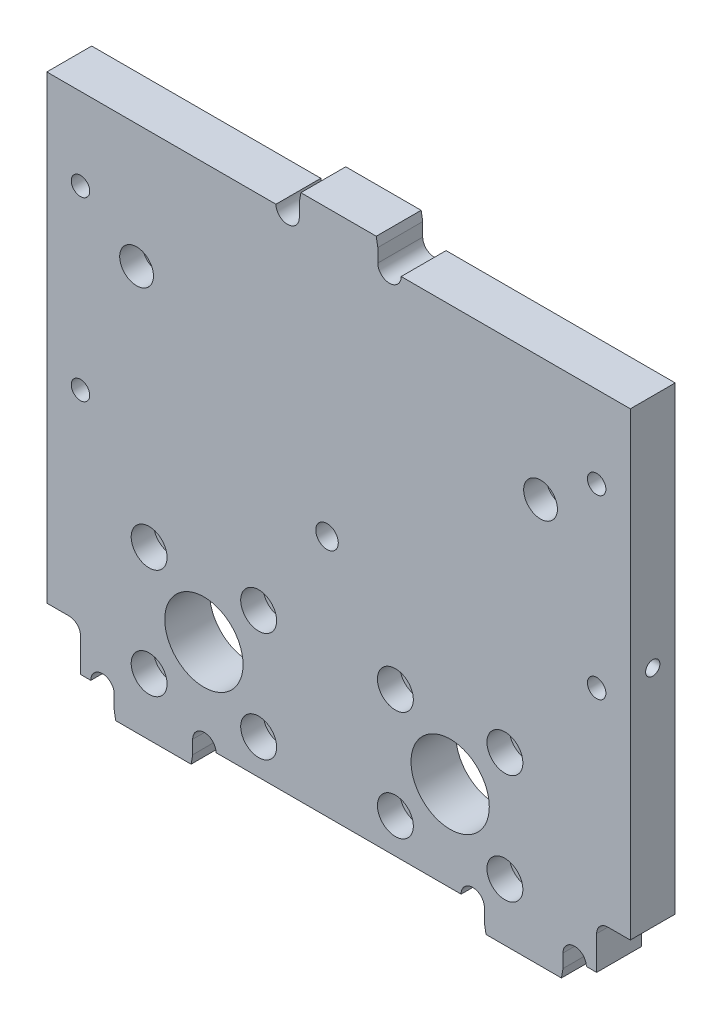
SolidWorks part; units mm, degrees
material "PE High Density"
ref_plane "Front Plane" through (0, 0, 0) normal (0, 0, 1) x (1, 0, 0)
ref_plane "Top Plane" through (0, 0, 0) normal (0, 1, 0) x (1, 0, 0)
ref_plane "Right Plane" through (0, 0, 0) normal (1, 0, 0) x (0, 0, -1)
sketch "Sketch1" plane through (0, 0, 0) normal (0, 0, 1) x (1, 0, 0)
  line L1 (-82.55, -71.4375) -> (82.55, -71.4375)
  line L2 (-82.55, -71.4375) -> (-82.55, 71.4375)
  line L3 (-82.55, 71.4375) -> (82.55, 71.4375)
  line L4 (82.55, -71.4375) -> (82.55, 71.4375)
  line L5 (-82.55, -71.4375) -> (82.55, 71.4375) construction
  line L6 (-82.55, 71.4375) -> (82.55, -71.4375) construction
  point P0 (0, 0)
  dimension "D1" = 165.1
  dimension "D2" = 142.875
extrude "Boss-Extrude1" add sketch "Sketch1" along normal blind 12.7
sketch "Sketch2" plane through (0, 0, 12.7) normal (0, 0, 1) x (1, 0, 0)
  line L0 (82.55, 71.4375) -> (-82.55, 71.4375) construction
  line L1 (-11.1125, 71.4375) -> (11.1125, 71.4375)
  line L2 (-11.1125, 71.4375) -> (-11.1125, 75.2475)
  line L3 (-10.6646, 77.7875) -> (10.6646, 77.7875)
  line L4 (11.1125, 71.4375) -> (11.1125, 75.2475)
  line L5 (10.6646, 77.7875) -> (11.1125, 75.2475)
  line L6 (-10.6646, 77.7875) -> (-11.1125, 75.2475)
  line L7 (82.55, -71.4375) -> (82.55, 71.4375) construction
  point P6 (0, 77.7875)
  dimension "D3" = 170
  dimension "D4" = 170
  dimension "D5" = 3.81
  dimension "D1" = 71.4375
  dimension "D2" = 6.35
extrude "Boss-Extrude2" add sketch "Sketch2" against normal up to surface (12.7 mm away) up to face at (0, 0, 0)
sketch "Sketch4" plane through (0, 0, 12.7) normal (0, 0, 1) x (1, 0, 0)
  line L0 (-11.1125, 71.4375) -> (-82.55, 71.4375) construction
  line L1 (-11.1125, 75.2475) -> (-11.1125, 71.4375) construction
  line L2 (-82.55, 71.4375) -> (82.55, 71.4375) construction
  line L3 (0, 77.7875) -> (0, 0) construction
  line L4 (10.6646, 77.7875) -> (-10.6646, 77.7875) construction
  line L5 (-17.7165, 71.4375) -> (-11.1125, 71.4375)
  line L6 (11.1125, 71.4375) -> (17.7165, 71.4375)
  arc A0 (-17.7165, 71.4375) -> (-11.1125, 71.4375) centre (-14.4145, 71.4375) ccw
  arc A1 (17.7165, 71.4375) -> (11.1125, 71.4375) centre (14.4145, 71.4375) cw
  dimension "D1" = 6.604
  dimension "D2" = 3.302
extrude "Cut-Extrude1" cut sketch "Sketch4" against normal up to next contours A1 L6 | A0 L5
sketch "Sketch5" plane through (0, 0, 12.7) normal (0, 0, 1) x (1, 0, 0)
  line L0 (-82.55, -71.4375) -> (82.55, -71.4375) construction
  line L1 (63.5, -71.4375) -> (41.275, -71.4375)
  line L2 (63.5, -71.4375) -> (63.5, -75.2475)
  line L3 (63.0521, -77.7875) -> (41.7229, -77.7875)
  line L4 (41.275, -71.4375) -> (41.275, -75.2475)
  line L5 (82.55, -71.4375) -> (82.55, 71.4375) construction
  line L6 (41.275, -75.2475) -> (41.7229, -77.7875)
  line L7 (63.5, -75.2475) -> (63.0521, -77.7875)
  dimension "D1" = 22.225
  dimension "D2" = 6.35
  dimension "D3" = 19.05
  dimension "D4" = 170
  dimension "D5" = 170
  dimension "D6" = 3.81
extrude "Boss-Extrude3" add sketch "Sketch5" against normal up to surface (12.7 mm away) up to face at (0, 48.768, 0)
hole_wizard "#21 (0.159) Diameter Hole2" positions "Sketch32" profile "Sketch33" hole size "#21" standard "ANSI Inch"
sketch "Sketch32" plane through (82.55, 0, 0) normal (1, 0, 0) x (0, 0, -1)
  line L0 (-12.7, -71.4375) -> (0, -71.4375) construction
  point P0 (-6.35, 4.7625)
  point P5 (-6.35, -71.4375)
  dimension "D1" = 76.2
sketch "Sketch33" plane through (82.55, 4.7625, 6.35) normal (0, 1, 0) x (0, 0, -1)
  line L0 (0, 0) -> (0, 23.4383)
  line L1 (0, 23.4383) -> (2.0193, 22.225)
  line L2 (2.0193, 22.225) -> (2.0193, 0)
  line L5 (2.0193, 0) -> (0, 0)
  line L10 (0, 23.4383) -> (-2.0193, 22.225) construction
  line L11 (0, -6.35) -> (0, 107.95) construction
  dimension "Hole Dia." = 4.0386
  dimension "Hole Depth" = 22.225
  dimension "Drill Angle" = 118
hole_wizard "#21 (0.159) Diameter Hole3" positions "Sketch34" profile "Sketch35" hole size "#21" standard "ANSI Inch"
sketch "Sketch34" plane through (-82.55, 0, 0) normal (-1, 0, 0) x (0, 0, 1)
  point P0 (6.35, 4.7625)
sketch "Sketch35" plane through (-82.55, 4.7625, 6.35) normal (0, 1, 0) x (0, 0, 1)
  line L0 (0, 0) -> (0, 23.4383)
  line L1 (0, 23.4383) -> (2.0193, 22.225)
  line L2 (2.0193, 22.225) -> (2.0193, 0)
  line L5 (2.0193, 0) -> (0, 0)
  line L10 (0, 23.4383) -> (-2.0193, 22.225) construction
  line L11 (0, -6.35) -> (0, 107.95) construction
  dimension "Hole Dia." = 4.0386
  dimension "Hole Depth" = 22.225
  dimension "Drill Angle" = 118
sketch "Sketch6" plane through (0, 0, 12.7) normal (0, 0, 1) x (1, 0, 0)
  line L0 (-82.55, -71.4375) -> (41.275, -71.4375) construction
  line L1 (82.55, -71.4375) -> (0, -71.4375) construction
  line L2 (34.671, -71.4375) -> (41.275, -71.4375)
  line L3 (52.3875, -77.7875) -> (52.3875, 71.4375) construction
  line L4 (41.7229, -77.7875) -> (63.0521, -77.7875) construction
  line L5 (82.55, 71.4375) -> (17.7165, 71.4375) construction
  line L6 (63.5, -71.4375) -> (70.104, -71.4375)
  arc A0 (41.275, -71.4375) -> (34.671, -71.4375) centre (37.973, -71.4375) ccw
  arc A1 (63.5, -71.4375) -> (70.104, -71.4375) centre (66.802, -71.4375) cw
  dimension "D1" = 6.604
  dimension "D2" = 3.302
extrude "Cut-Extrude2" cut sketch "Sketch6" against normal up to surface (12.7 mm away) up to face at (17.4625, 7.5706, 0)
mirror "Mirror1" about plane through (0, 0, 0) normal (1, 0, 0) of "Boss-Extrude3", "Cut-Extrude2"
sketch "Sketch21" plane through (0, 0, 12.7) normal (0, 0, 1) x (1, 0, 0)
  line L1 (-82.55, 71.4375) -> (-82.55, -71.4375) construction
  line L2 (-34.671, -71.4375) -> (34.671, -71.4375) construction
  line L3 (-82.55, -71.4375) -> (-70.104, -71.4375) construction
  line L4 (-53.594, -30.5435) -> (-22.606, -30.5435) construction
  line L5 (-53.594, -30.5435) -> (-53.594, -61.5315) construction
  line L6 (-53.594, -61.5315) -> (-22.606, -61.5315) construction
  line L7 (-22.606, -30.5435) -> (-22.606, -61.5315) construction
  line L8 (16.0799, -30.5435) -> (47.0679, -30.5435) construction
  line L9 (16.0799, -30.5435) -> (16.0799, -61.5315) construction
  line L10 (16.0799, -61.5315) -> (47.0679, -61.5315) construction
  line L11 (47.0679, -30.5435) -> (47.0679, -61.5315) construction
  circle A0 centre (-57.15, 36.5125) radius 4.7752
  circle A1 centre (57.15, 36.5125) radius 4.7752
  circle A2 centre (-57.15, 36.5125) radius 114.3 construction
  circle A3 centre (-57.15, 36.5125) radius 66.675 construction
  circle A4 centre (-3.263, -2.7527) radius 3.1877
  circle A5 centre (-3.263, -2.7527) radius 55.5625 construction
  circle A6 centre (-38.1, -46.0375) radius 11.0754
  circle A7 centre (31.5739, -46.0375) radius 11.0754
  circle A8 centre (-38.1, -46.0375) radius 21.9118 construction
  circle A9 centre (-53.594, -30.5435) radius 5.08
  circle A10 centre (-22.606, -30.5435) radius 5.08
  circle A11 centre (-22.606, -61.5315) radius 5.08
  circle A12 centre (-53.594, -61.5315) radius 5.08
  circle A13 centre (31.5739, -46.0375) radius 21.9118 construction
  circle A14 centre (16.0799, -30.5435) radius 5.08
  circle A15 centre (47.0679, -30.5435) radius 5.08
  circle A16 centre (47.0679, -61.5315) radius 5.08
  circle A17 centre (16.0799, -61.5315) radius 5.08
  dimension "D1" = 228.6
  dimension "D3" = 9.5504
  dimension "D4" = 9.5504
  dimension "D6" = 133.35
  dimension "D7" = 6.3754
  dimension "D8" = 111.125
  dimension "D9" = 22.1508
  dimension "D10" = 22.1508
  dimension "D15" = 10.16
  dimension "D5" = 25.4
  dimension "D11" = 25.4
  dimension "D12" = 44.45
  dimension "D13" = 30.988
  dimension "D14" = 30.988
  dimension "D16" = 30.988
  dimension "D2" = 107.95
extrude "Cut-Extrude10" cut sketch "Sketch21" against normal blind 6.35 contours A12 | A0 | A9 | A10 | A11 | A6 | A4 | A7 | A14 | A15 | A16 | A17 | A1
hole_wizard "#8 Clearance Hole1" positions "Sketch22" profile "Sketch23" hole size "#8" standard "ANSI Inch"
sketch "Sketch22" plane through (0, 0, 12.7) normal (0, 0, 1) x (1, 0, 0)
  point P0 (-57.15, 36.5125)
  point P3 (57.15, 36.5125)
  point P6 (-3.263, -2.7527)
sketch "Sketch23" plane through (-57.15, 36.5125, 12.7) normal (1, 0, 0) x (0, -1, 0)
  line L0 (0, 0) -> (0, 20.4007)
  line L1 (0, 20.4007) -> (2.2479, 19.05)
  line L2 (2.2479, 19.05) -> (2.2479, 0)
  line L5 (2.2479, 0) -> (0, 0)
  line L10 (0, 20.4007) -> (-2.2479, 19.05) construction
  line L11 (0, -6.35) -> (0, 107.95) construction
  dimension "Hole Dia." = 4.4958
  dimension "Hole Depth" = 19.05
  dimension "Drill Angle" = 118
hole_wizard "M3 Clearance Hole1" positions "Sketch24" profile "Sketch25" hole size "M3" standard "ANSI Metric"
sketch "Sketch24" plane through (0, 0, 12.7) normal (0, 0, 1) x (1, 0, 0)
  point P0 (-53.594, -30.5435)
  point P3 (-22.606, -30.5435)
  point P6 (-22.606, -61.5315)
  point P9 (-53.594, -61.5315)
  point P12 (16.0799, -61.5315)
  point P15 (16.0799, -30.5435)
  point P18 (47.0679, -30.5435)
  point P21 (47.0679, -61.5315)
sketch "Sketch25" plane through (-53.594, -30.5435, 12.7) normal (1, 0, 0) x (0, -1, 0)
  line L0 (0, 0) -> (0, 20.0715)
  line L1 (0, 20.0715) -> (1.7, 19.05)
  line L2 (1.7, 19.05) -> (1.7, 0)
  line L5 (1.7, 0) -> (0, 0)
  line L10 (0, 20.0715) -> (-1.7, 19.05) construction
  line L11 (0, -6.35) -> (0, 107.95) construction
  dimension "Hole Dia." = 3.4
  dimension "Hole Depth" = 19.05
  dimension "Drill Angle" = 118
sketch "Sketch28" plane through (0, 0, 12.7) normal (0, 0, 1) x (1, 0, 0)
  circle A2 centre (31.5739, -46.0375) radius 11.0754 construction
  circle A3 centre (-38.1, -46.0375) radius 11.0754 construction
  circle A4 centre (31.5739, -46.0375) radius 11.0754
  circle A5 centre (-38.1, -46.0375) radius 11.0754
extrude "Cut-Extrude11" cut sketch "Sketch28" against normal up to surface (12.7 mm away) up to face at (-55.294, -30.5435, 0)
sketch "Sketch29" plane through (0, 0, 12.7) normal (0, 0, 1) x (1, 0, 0)
  line L1 (-82.55, -71.4375) -> (-73.025, -71.4375)
  line L2 (-82.55, -71.4375) -> (-82.55, -58.7375)
  line L3 (-82.55, -58.7375) -> (-73.025, -58.7375)
  line L4 (-73.025, -71.4375) -> (-73.025, -58.7375)
  line L5 (82.55, -71.4375) -> (73.025, -71.4375)
  line L6 (82.55, -71.4375) -> (82.55, -58.7375)
  line L7 (82.55, -58.7375) -> (73.025, -58.7375)
  line L8 (73.025, -71.4375) -> (73.025, -58.7375)
  dimension "D1" = 12.7
  dimension "D2" = 9.525
extrude "Cut-Extrude12" cut sketch "Sketch29" against normal through all
fillet "Fillet1" radius 3.175 2 edges at (73.025, -58.7375, 6.35) (-73.025, -58.7375, 6.35)
hole_wizard "#5 (0.2055) Diameter Hole1" positions "Sketch36" profile "Sketch37" hole size "#5" standard "ANSI Inch" end condition through all
sketch "Sketch36" plane through (0, 0, 0) normal (0, 0, -1) x (-1, 0, 0)
  line L1 (-82.55, -58.7375) -> (-82.55, 71.4375) construction
  line L2 (-82.55, 71.4375) -> (-17.7165, 71.4375) construction
  point P0 (-73.025, 48.26)
  point P2 (73.025, 48.26)
  point P4 (73.025, -1.74)
  point P6 (-73.025, -1.74)
  point P14 (0, 0)
  point P15 (0, 0)
  point P16 (0, 0)
  point P17 (0, 0)
  dimension "D1" = 146.05
  dimension "D2" = 9.525
  dimension "D3" = 23.1775
  dimension "D4" = 50
sketch "Sketch37" plane through (73.025, 48.26, 0) normal (1, 0, 0) x (0, 1, 0)
  line L0 (0, 0) -> (0, 12.7)
  line L1 (0, 12.7) -> (2.6098, 12.7)
  line L2 (2.6098, 12.7) -> (2.6098, 0)
  line L5 (2.6098, 0) -> (0, 0)
  line L11 (0, -6.35) -> (0, 107.95) construction
  dimension "Thru Hole Dia." = 5.2197
  dimension "Thru Hole Depth" = 12.7
equation "\"D4@Sketch2\"=\"D3@Sketch2\""
equation "\"D2@Sketch4\"=\"D1@Sketch4\"/2"
equation "\"D2@Sketch6\"=\"D1@Sketch6\"/2"
equation "\"D4@Sketch21\"=\"D3@Sketch21\""
equation "\"D5@Sketch21\"=(6.5-\"D1@Sketch21\"/2)/2"
equation "\"D6@Sketch21\"=4.5+.75"
equation "\"D8@Sketch21\"=4+.375"
equation "\"D9@Sketch21\"=22.1mm+.002"
equation "\"D10@Sketch21\"=\"D9@Sketch21\""
equation "\"D14@Sketch21\"=\"D13@Sketch21\""
equation "\"D16@Sketch21\"=\"D13@Sketch21\""
equation "\"D2@Sketch1\"=6.000in-.375"
equation "\"D2@Sketch36\"=(6.5-\"D1@Sketch36\")/2"
equation "\"D4@Sketch36\"=50mm"
